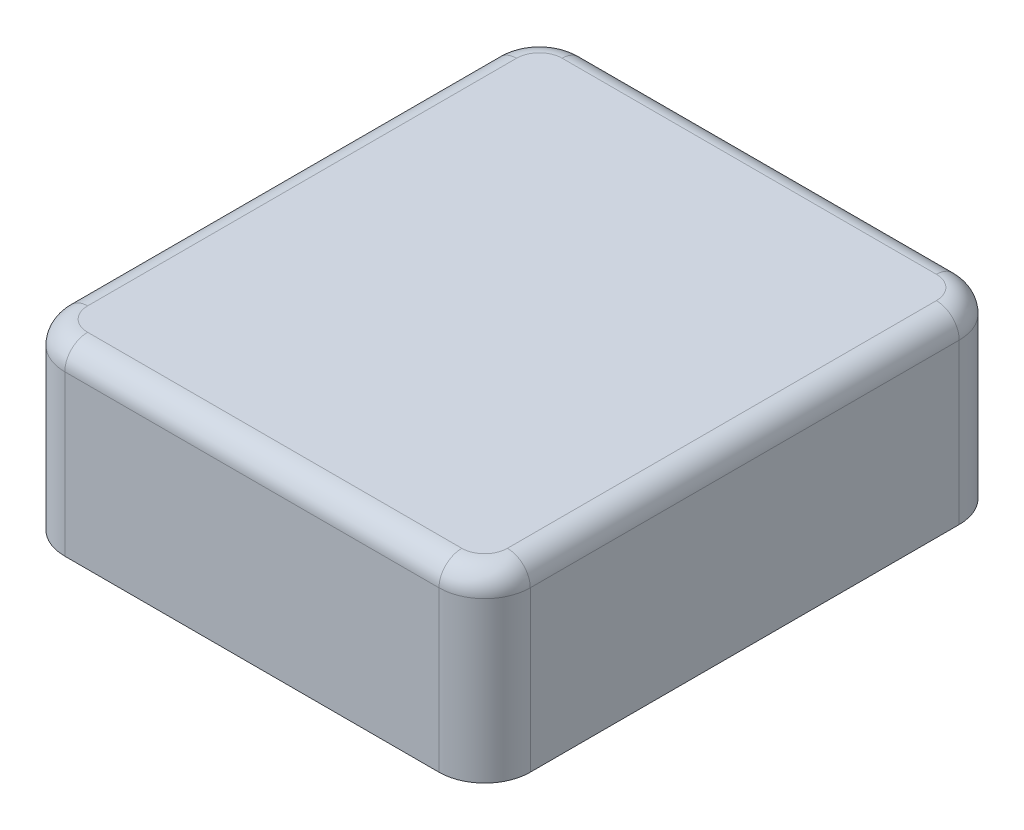
SolidWorks part; units mm, degrees
ref_plane "Front Plane" through (0, 0, 0) normal (0, 0, 1) x (1, 0, 0)
ref_plane "Top Plane" through (0, 0, 0) normal (0, 1, 0) x (1, 0, 0)
ref_plane "Right Plane" through (0, 0, 0) normal (1, 0, 0) x (0, 0, -1)
sketch "Sketch1" plane through (0, 0, 0) normal (0, 0, 1) x (1, 0, 0)
  line L1 (32.385, -12.7) -> (-32.385, -12.7)
  line L2 (32.385, -12.7) -> (32.385, 12.7)
  line L3 (32.385, 12.7) -> (-32.385, 12.7)
  line L4 (-32.385, -12.7) -> (-32.385, 12.7)
  line L5 (32.385, -12.7) -> (-32.385, 12.7) construction
  line L6 (32.385, 12.7) -> (-32.385, -12.7) construction
  point P0 (0, 0)
  dimension "D1" = 25.4
  dimension "D2" = 64.77
extrude "Boss-Extrude1" add sketch "Sketch1" against normal mid plane 72.39
fillet "Fillet1" radius 6.35 4 edges at (-32.385, 0, -36.195) (32.385, 0, -36.195) (32.385, 0, 36.195) (-32.385, 0, 36.195)
fillet "Fillet2" radius 3.175 8 edges at (30.5251, 12.7, 34.3351) (32.385, 12.7, 0) (30.5251, 12.7, -34.3351) (0, 12.7, -36.195) (-30.5251, 12.7, -34.3351) (-32.385, 12.7, 0) (-30.5251, 12.7, 34.3351) (0, 12.7, 36.195)
shell "Shell2" thickness 1.524
sketch "Sketch2" plane through (0, 0, 0) normal (0, 0, 1) x (1, 0, 0)
  line L0 (-30.861, -4.4231) -> (30.861, -4.4231)
  line L1 (-30.861, 11.176) -> (-30.861, -11.176) construction
  line L2 (30.861, -11.176) -> (30.861, 11.176) construction
extrude "Extrude-Thin1" add sketch "Sketch2" along normal up to next and the other way up to next thin thin type mid plane wall 1.524
sketch "Sketch3" plane through (0, -12.7, 0) normal (0, -1, 0) x (1, 0, 0)
  line L0 (0, 43.0535) -> (0, -43.0535) construction
  line L1 (32.385, -29.845) -> (32.385, 29.845) construction
  line L2 (45.085, -6.35) -> (32.385, -6.35)
  line L3 (45.085, -6.35) -> (45.085, 6.35)
  line L4 (45.085, 6.35) -> (32.385, 6.35)
  line L5 (32.385, -6.35) -> (32.385, 6.35)
  line L6 (45.085, -6.35) -> (32.385, 6.35) construction
  line L7 (45.085, 6.35) -> (32.385, -6.35) construction
  line L8 (-45.085, 6.35) -> (-32.385, -6.35) construction
  line L9 (-45.085, -6.35) -> (-32.385, 6.35) construction
  line L10 (-32.385, -6.35) -> (-32.385, 6.35)
  line L11 (-45.085, 6.35) -> (-32.385, 6.35)
  line L12 (-45.085, -6.35) -> (-45.085, 6.35)
  line L13 (-45.085, -6.35) -> (-32.385, -6.35)
  circle A0 centre (38.735, 0) radius 2.286
  circle A1 centre (-38.735, 0) radius 2.286
  point P2 (38.735, 0)
  dimension "D3" = 4.572
  dimension "D1" = 12.7
  dimension "D2" = 12.7
extrude "Boss-Extrude2" [suppressed] add sketch "Sketch3" against normal blind 3.175
fillet "Fillet3" [suppressed] radius 3.175
fillet "Fillet4" [suppressed] radius 0.762
sketch "Sketch4" plane through (0, 0, -36.195) normal (0, 0, 1) x (1, 0, 0)
  circle A3 centre (12.0018, -7.7058) radius 2.159
  circle A26 centre (12.0018, -7.7058) radius 1.905 construction
  point P1 (12.0018, -7.7058)
  dimension "D1" = 3.81
  dimension "D2" = 0.254
extrude "Cut-Extrude2" cut sketch "Sketch4" along normal up to next
